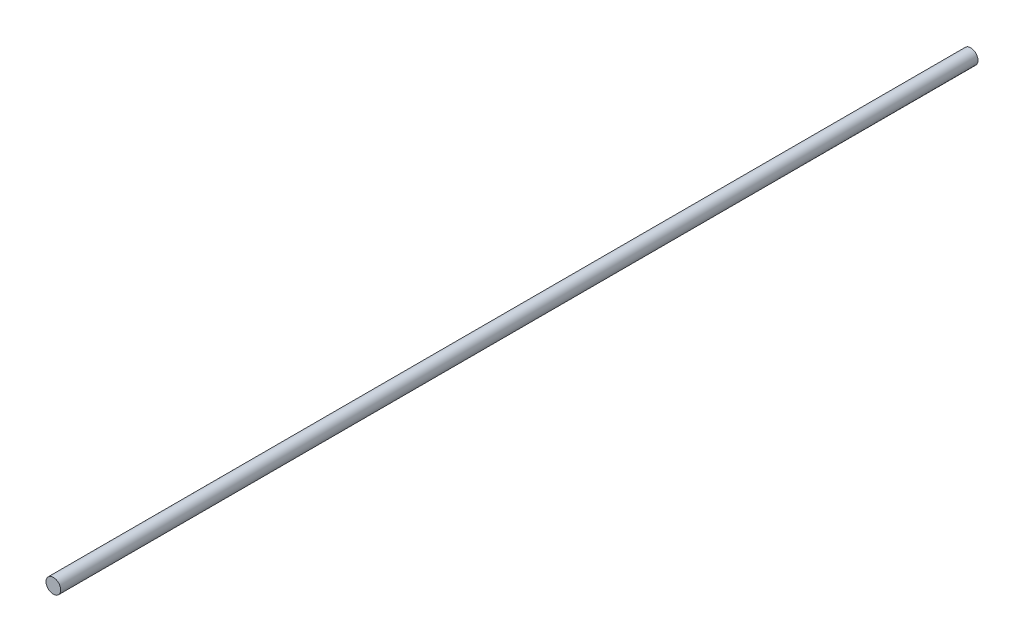
SolidWorks part; units mm, degrees
material "Plain Carbon Steel"
ref_plane "Front Plane" through (0, 0, 0) normal (0, 0, 1) x (1, 0, 0)
ref_plane "Top Plane" through (0, 0, 0) normal (0, 1, 0) x (1, 0, 0)
ref_plane "Right Plane" through (0, 0, 0) normal (1, 0, 0) x (0, 0, -1)
sketch "Sketch1" plane through (0, 0, 0) normal (0, 0, 1) x (1, 0, 0)
  circle A0 centre (0, 0) radius 0.4064
  dimension "D1" = 0.8128
extrude "Boss-Extrude1" add sketch "Sketch1" against normal blind 50.8
